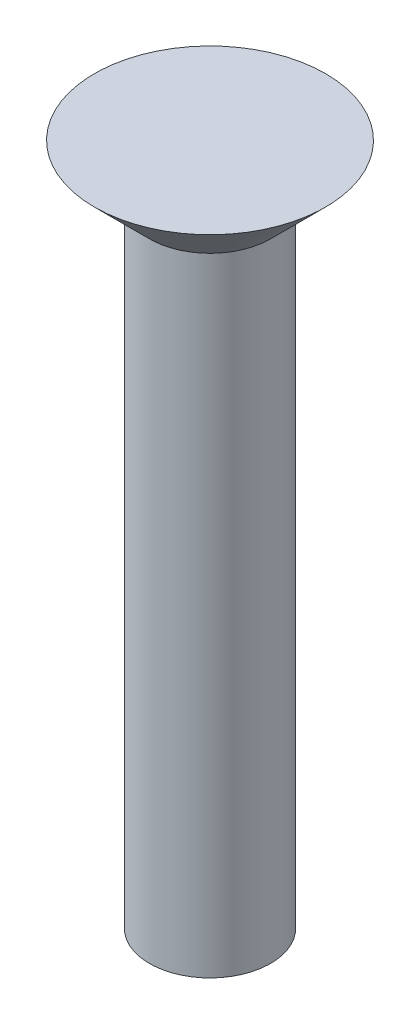
SolidWorks part; units mm, degrees
ref_plane "Front Plane" through (0, 0, 0) normal (0, 0, 1) x (1, 0, 0)
ref_plane "Top Plane" through (0, 0, 0) normal (0, 1, 0) x (1, 0, 0)
ref_plane "Right Plane" through (0, 0, 0) normal (1, 0, 0) x (0, 0, -1)
sketch "Sketch1" plane through (0, 0, 0) normal (0, 0, 1) x (1, 0, 0)
  line L0 (0, -9.3) -> (0, 9.3)
  line L1 (0, 9.3) -> (3.15, 9.3)
  line L2 (3.15, 9.3) -> (1.65, 7.8)
  line L3 (1.65, 7.8) -> (1.65, -9.3)
  line L4 (1.65, -9.3) -> (0, -9.3)
  point P3 (3.4994, 3.456)
  point P7 (1.65, 6.0161)
  dimension "D1" = 1.65
  dimension "D2" = 18.6
  dimension "D3" = 3.15
  dimension "D4" = 45
revolve "Revolve1" add sketch "Sketch1" angle 360 about L0
